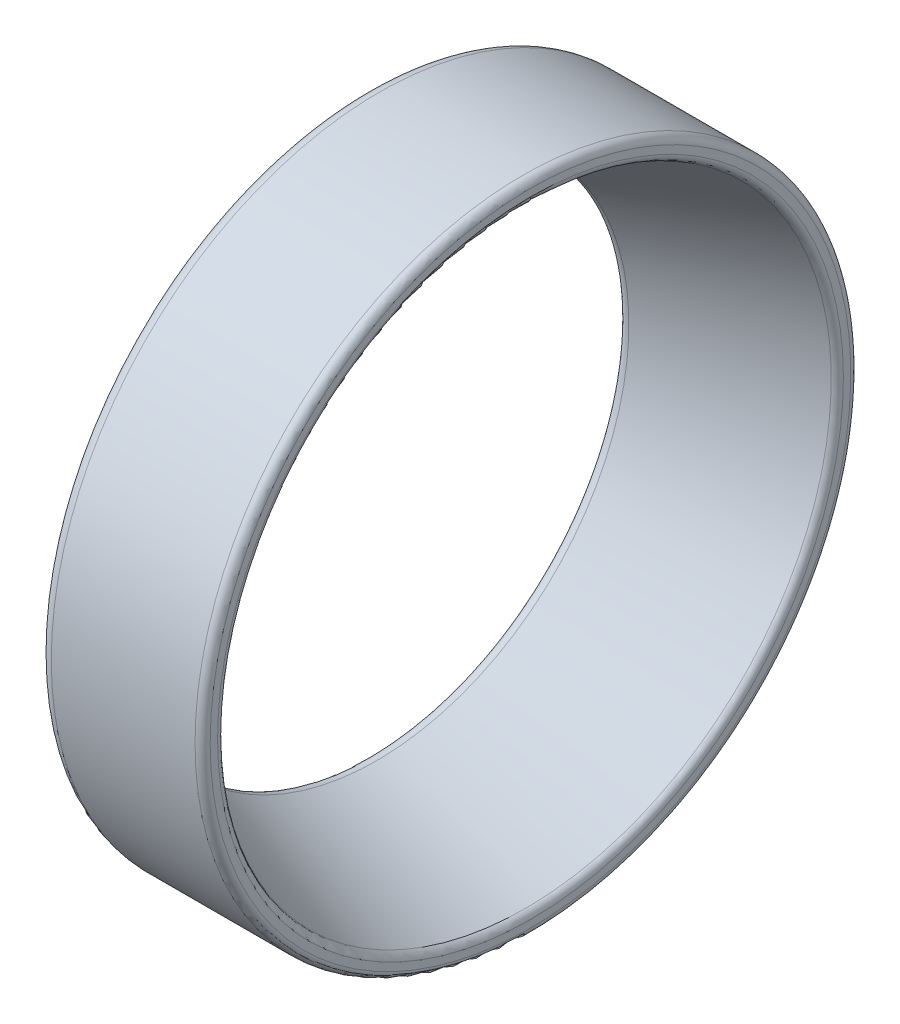
SolidWorks part; units mm, degrees
ref_plane "Plan1" through (0, 0, 0) normal (0, 0, 1) x (1, 0, 0)
ref_plane "Plan2" through (0, 0, 0) normal (0, 1, 0) x (1, 0, 0)
ref_plane "Plan3" through (0, 0, 0) normal (1, 0, 0) x (0, 0, -1)
sketch "Esquisse1" plane through (0, 0, 0) normal (0, 0, 1) x (1, 0, 0)
  line L0 (-15.2964, 26) -> (-3.8964, 26)
  line L1 (-3.2964, 25.4) -> (-3.2964, 24.811)
  line L2 (-3.6933, 24.2464) -> (-15.4933, 20.0024)
  line L3 (-16.2964, 20.5669) -> (-16.2964, 25)
  line L4 (-17.9901, 0) -> (10.4363, 0) construction
  line L7 (-7.9556, 14.8702) -> (-3.5464, 0) construction
  line L9 (-5.2883, 23.6728) -> (-14.8261, 20.2423) construction
  line L10 (-12.8887, 13.7086) -> (-3.0226, 16.0318) construction
  line L11 (8.3922, 23.5728) -> (-71.107, 0) construction
  arc A0 (-15.2964, 26) -> (-16.2964, 25) centre (-15.2964, 25) ccw
  arc A1 (-15.4933, 20.0024) -> (-16.2964, 20.5669) centre (-15.6964, 20.5669) cw
  arc A2 (-3.2964, 24.811) -> (-3.6933, 24.2464) centre (-3.8964, 24.811) cw
  arc A3 (-3.8964, 26) -> (-3.2964, 25.4) centre (-3.8964, 25.4) cw
  point P9 (-7.9556, 14.8702)
  point P22 (-3.2964, 24.3892)
  point P25 (-3.2964, 26)
  dimension "D4" = 1
  dimension "D6" = 0.6
  dimension "D1" = 13
  dimension "D2" = 26
  dimension "D3" = 12.75
  dimension "D5" = 1.6108
revolve "Base-Révolution" add sketch "Esquisse1" angle 360 about L4
